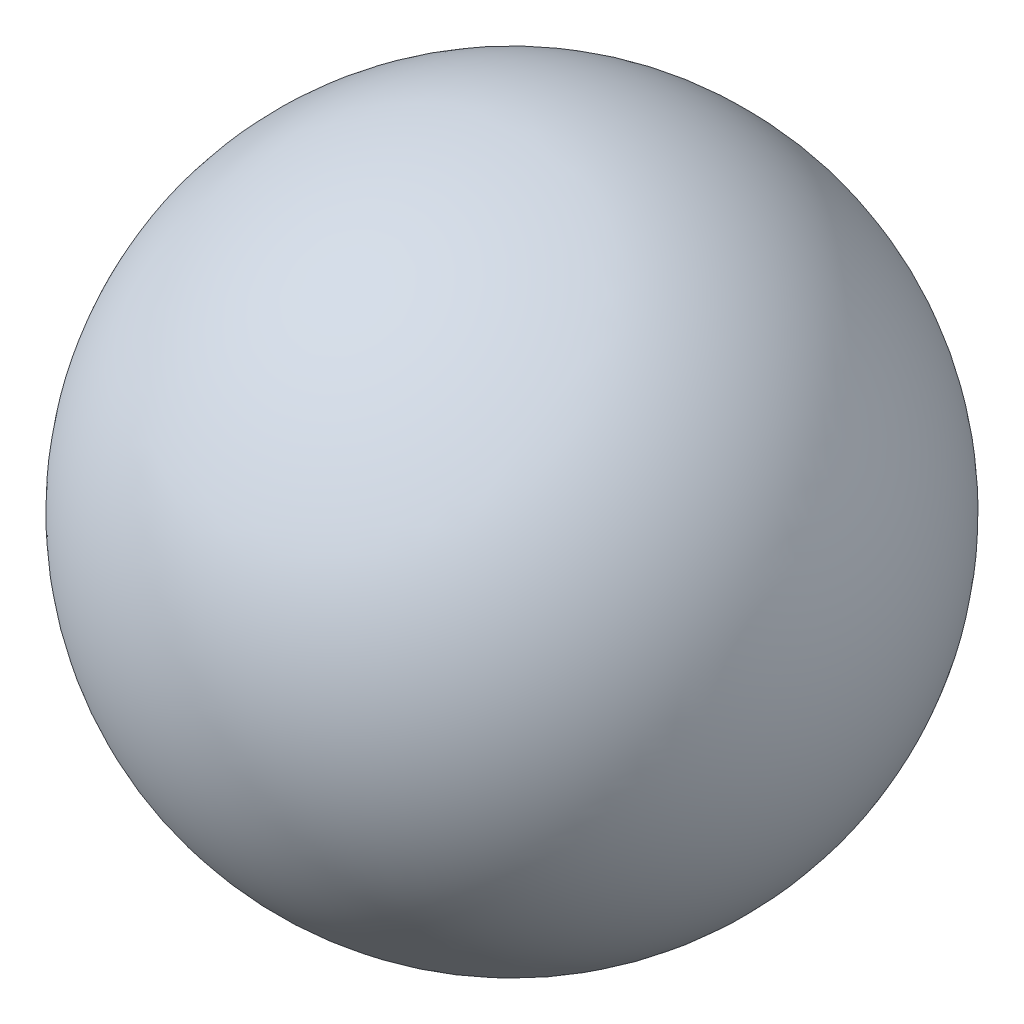
SolidWorks part; units mm, degrees
ref_plane "Front Plane" through (0, 0, 0) normal (0, 0, 1) x (1, 0, 0)
ref_plane "Top Plane" through (0, 0, 0) normal (0, 1, 0) x (1, 0, 0)
ref_plane "Right Plane" through (0, 0, 0) normal (1, 0, 0) x (0, 0, -1)
sketch "Sketch1" plane through (0, 0, 0) normal (0, 0, 1) x (1, 0, 0)
  line L0 (-10.3648, 0) -> (11.6352, 0)
  arc A0 (11.6352, 0) -> (-10.3648, 0) centre (0.6352, 0) cw
  dimension "D1" = 22
revolve "Revolve1" add sketch "Sketch1" angle 360 about L0
